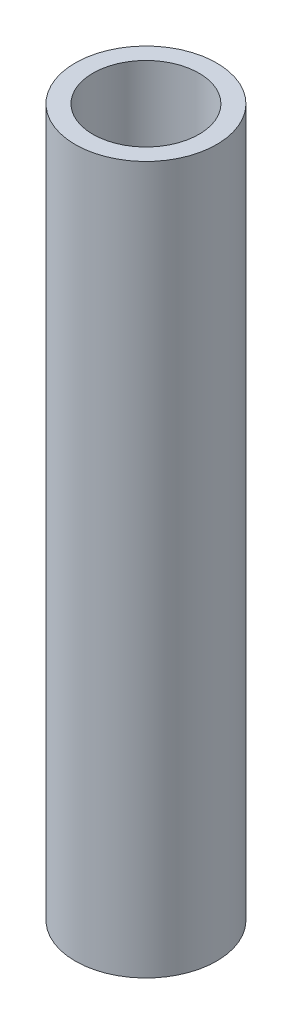
SolidWorks part; units mm, degrees
material "Hexcel AS4C (3000 丝)"
ref_plane "前视基准面" through (0, 0, 0) normal (0, 0, 1) x (1, 0, 0)
ref_plane "上视基准面" through (0, 0, 0) normal (0, 1, 0) x (1, 0, 0)
ref_plane "右视基准面" through (0, 0, 0) normal (1, 0, 0) x (0, 0, -1)
sketch "草图1" plane through (0, 0, 0) normal (0, 1, 0) x (1, 0, 0)
  circle A0 centre (0, 0) radius 4
  circle A1 centre (0, 0) radius 3
  dimension "D1" = 6
  dimension "D2" = 8
extrude "凸台-拉伸1" add sketch "草图1" along normal blind 40
